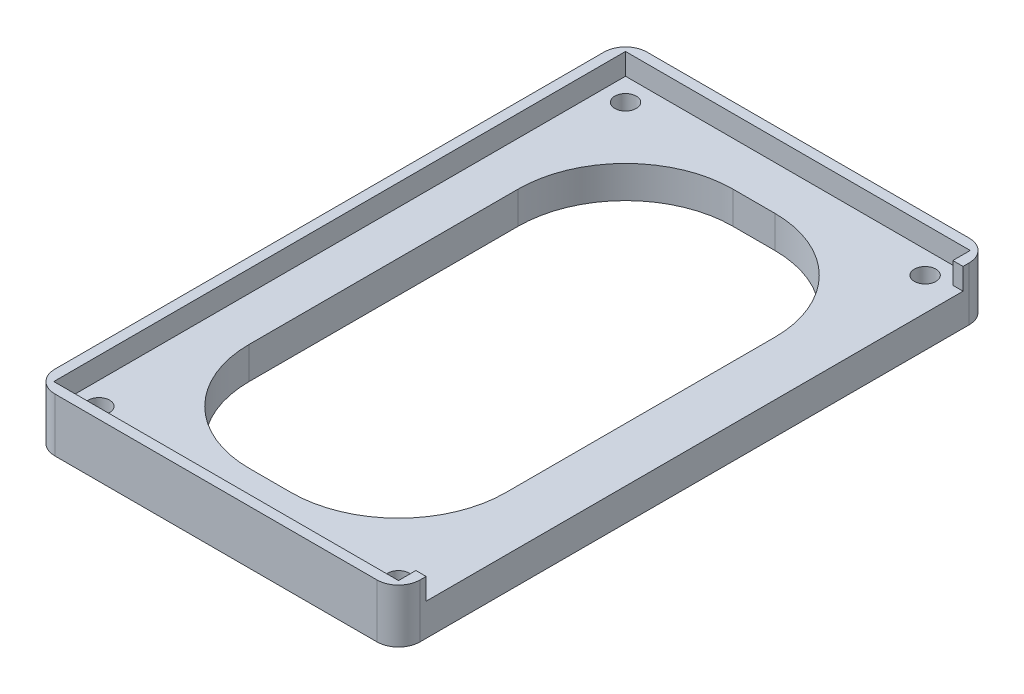
SolidWorks part; units mm, degrees
ref_plane "前视基准面" through (0, 0, 0) normal (0, 0, 1) x (1, 0, 0)
ref_plane "上视基准面" through (0, 0, 0) normal (0, 1, 0) x (1, 0, 0)
ref_plane "右视基准面" through (0, 0, 0) normal (1, 0, 0) x (0, 0, -1)
other "Configuration Table"
sketch "草图1" plane through (0, 0, 0) normal (0, 1, 0) x (1, 0, 0)
  line L1 (0, 0) -> (34, 0)
  line L2 (0, 0) -> (0, 55.14)
  line L3 (0, 55.14) -> (34, 55.14)
  line L4 (34, 0) -> (34, 55.14)
  dimension "D1" = 34
  dimension "D2" = 55.14
extrude "凸台-拉伸1" add sketch "草图1" along normal blind 5
sketch "草图2" plane through (0, 5, 0) normal (0, 1, 0) x (1, 0, 0)
  line L0 (0.95, 54.19) -> (33.05, 54.19)
  line L2 (0, 55.14) -> (0, 0)
  line L3 (0, 0) -> (34, 0)
  line L4 (34, 55.14) -> (34, 0)
  line L5 (33.05, 54.19) -> (33.05, 0.95)
  line L6 (0.95, 0.95) -> (33.05, 0.95)
  line L7 (0.95, 54.19) -> (0.95, 0.95)
  line L8 (0, 55.14) -> (34, 55.14) construction
  dimension "D1" = 0.95
extrude "切除-拉伸1" cut sketch "草图2" against normal blind 2 contours L0 L7 L6 L5
sketch "草图3" plane through (34, 0, 0) normal (1, 0, 0) x (0, 0, -1)
  line L0 (0, 5) -> (55.14, 5) construction
  line L1 (52.57, 10) -> (2.57, 10)
  line L2 (52.57, 10) -> (52.57, 0)
  line L3 (52.57, 0) -> (2.57, 0)
  line L4 (2.57, 10) -> (2.57, 0)
  line L5 (52.57, 10) -> (2.57, 0) construction
  line L6 (52.57, 0) -> (2.57, 10) construction
  line L7 (0, 0) -> (55.14, 0) construction
  point P0 (27.57, 5)
  dimension "D1" = 50
extrude "切除-拉伸2" cut sketch "草图3" against normal blind 2
fillet "圆角3" radius 2 1 edges at (0, 2.5, 0)
fillet "圆角4" radius 2 1 edges at (0, 2.5, -55.14)
fillet "圆角5" radius 2 1 edges at (34, 2.5, -55.14)
fillet "圆角6" radius 2 1 edges at (34, 2.5, 0)
sketch "草图5" plane through (0, 3, 0) normal (0, 1, 0) x (1, 0, 0)
  line L0 (17, -945.81) -> (17, 49054.19) construction
  line L1 (0.95, 54.19) -> (3.05, 54.19)
  line L2 (0.95, 54.19) -> (0.95, 52.09)
  line L3 (0.95, 52.09) -> (3.05, 52.09)
  line L4 (3.05, 54.19) -> (3.05, 52.09)
  line L6 (-999.05, 27.57) -> (49000.95, 27.57) construction
  line L7 (0.95, 54.19) -> (0.95, 0.95) construction
  line L8 (0.95, 54.19) -> (33.05, 54.19) construction
  circle A0 centre (3.05, 52.09) radius 1
  circle A1 centre (3.05, 3.05) radius 1
  circle A2 centre (30.95, 3.05) radius 1
  circle A3 centre (30.95, 52.09) radius 1
  point P13 (0.95, 27.57)
  point P16 (17, 54.19)
  dimension "D3" = 2
  dimension "D1" = 2.1
  dimension "D2" = 2.1
extrude "切除-拉伸3" cut sketch "草图5" against normal blind 5 contours A2 | A3 | A0 | A1
sketch "草图6" plane through (0, 3, 0) normal (0, 1, 0) x (1, 0, 0)
  line L0 (5.05, 49.09) -> (5.05, 6.05)
  line L1 (3.05, 52.09) -> (30.95, 52.09)
  line L2 (3.05, 52.09) -> (3.05, 3.05)
  line L3 (3.05, 3.05) -> (30.95, 3.05)
  line L4 (30.95, 52.09) -> (30.95, 3.05)
  line L5 (6.05, 5.05) -> (6.2547, 5.05)
  line L6 (28.95, 50.09) -> (28.95, 5.05)
  line L7 (6.05, 50.09) -> (6.2547, 50.09)
  line L8 (10.05, 49.09) -> (10.05, 6.05)
  line L13 (5.05, 50.09) -> (7.2547, 50.09)
  line L14 (5.05, 50.09) -> (5.05, 5.05)
  line L15 (5.05, 5.05) -> (7.2547, 5.05)
  line L16 (7.2547, 49.09) -> (7.2547, 6.05)
  line L17 (11.05, 50.09) -> (11.2547, 50.09)
  line L18 (12.2547, 49.09) -> (12.2547, 6.05)
  line L19 (11.05, 5.05) -> (11.2547, 5.05)
  line L20 (15.05, 49.09) -> (15.05, 6.05)
  line L21 (16.05, 50.09) -> (16.2547, 50.09)
  line L22 (17.2547, 49.09) -> (17.2547, 6.05)
  line L23 (16.05, 5.05) -> (16.2547, 5.05)
  line L24 (20.05, 49.09) -> (20.05, 6.05)
  line L25 (21.05, 50.09) -> (21.2547, 50.09)
  line L26 (22.2547, 49.09) -> (22.2547, 6.05)
  line L27 (21.05, 5.05) -> (21.2547, 5.05)
  line L28 (25.05, 49.09) -> (25.05, 6.05)
  line L29 (26.05, 50.09) -> (26.2547, 50.09)
  line L30 (27.2547, 49.09) -> (27.2547, 6.05)
  line L31 (26.05, 5.05) -> (26.2547, 5.05)
  line L32 (5.05, 50.09) -> (28.95, 50.09) construction
  line L33 (5.05, 5.05) -> (28.95, 5.05) construction
  line L34 (5.05, 50.09) -> (5.05, 5.05) construction
  arc A0 (6.2547, 50.09) -> (7.2547, 49.09) centre (6.2547, 49.09) cw
  arc A1 (6.2547, 5.05) -> (7.2547, 6.05) centre (6.2547, 6.05) ccw
  arc A2 (6.05, 5.05) -> (5.05, 6.05) centre (6.05, 6.05) cw
  arc A3 (5.05, 49.09) -> (6.05, 50.09) centre (6.05, 49.09) cw
  arc A4 (26.2547, 50.09) -> (27.2547, 49.09) centre (26.2547, 49.09) cw
  arc A5 (25.05, 49.09) -> (26.05, 50.09) centre (26.05, 49.09) cw
  arc A6 (26.2547, 5.05) -> (27.2547, 6.05) centre (26.2547, 6.05) ccw
  arc A7 (26.05, 5.05) -> (25.05, 6.05) centre (26.05, 6.05) cw
  arc A8 (21.2547, 5.05) -> (22.2547, 6.05) centre (21.2547, 6.05) ccw
  arc A9 (20.05, 6.05) -> (21.05, 5.05) centre (21.05, 6.05) ccw
  arc A10 (21.2547, 50.09) -> (22.2547, 49.09) centre (21.2547, 49.09) cw
  arc A11 (20.05, 49.09) -> (21.05, 50.09) centre (21.05, 49.09) cw
  arc A12 (16.2547, 50.09) -> (17.2547, 49.09) centre (16.2547, 49.09) cw
  arc A13 (15.05, 49.09) -> (16.05, 50.09) centre (16.05, 49.09) cw
  arc A14 (16.2547, 5.05) -> (17.2547, 6.05) centre (16.2547, 6.05) ccw
  arc A15 (16.05, 5.05) -> (15.05, 6.05) centre (16.05, 6.05) cw
  arc A16 (11.2547, 5.05) -> (12.2547, 6.05) centre (11.2547, 6.05) ccw
  arc A17 (10.05, 6.05) -> (11.05, 5.05) centre (11.05, 6.05) ccw
  arc A18 (11.2547, 50.09) -> (12.2547, 49.09) centre (11.2547, 49.09) cw
  arc A19 (10.05, 49.09) -> (11.05, 50.09) centre (11.05, 49.09) cw
  dimension "D3" = 1
  dimension "D4" = 1
  dimension "D1" = 2
  dimension "D2" = 5
extrude "切除-拉伸5" cut sketch "草图6" against normal blind 5 contours A3 L0 A2 L5 A1 L16 A0 L7 | A19 L8 A17 L19 A16 L18 A18 L17 | A11 L24 A9 L27 A8 L26 A10 L25 | A7 L31 A6 L30 A4 L29 A5 L28 | L20 A15 L23 A14 L22 A12 L21 A13
sketch "草图7" plane through (0, 0, 0) normal (0, -1, 0) x (1, 0, 0)
  line L1 (3.3369, -4.5252) -> (27.9146, -4.5252)
  line L2 (3.3369, -4.5252) -> (3.3369, -50.6148)
  line L3 (3.3369, -50.6148) -> (27.9146, -50.6148)
  line L4 (27.9146, -4.5252) -> (27.9146, -50.6148)
extrude "凸台-拉伸3" add sketch "草图7" against normal blind 3
sketch "草图8" plane through (0, 0, 0) normal (0, -1, 0) x (1, 0, 0)
  line L0 (17, 0) -> (17, -3)
  line L1 (2, 0) -> (32, 0) construction
  line L3 (7, -6) -> (27, -6)
  line L4 (7, -6) -> (7, 0)
  line L5 (7, 0) -> (27, 0)
  line L6 (27, -6) -> (27, 0)
  line L7 (7, -6) -> (27, 0) construction
  line L8 (7, 0) -> (27, -6) construction
  dimension "D1" = 3
  dimension "D2" = 6
  dimension "D3" = 20
extrude "凸台-拉伸5" add sketch "草图8" along normal blind 5
sketch "草图9" plane through (0, 0, 0) normal (0, -1, 0) x (1, 0, 0)
  line L0 (17, -55.14) -> (17, -52.14)
  line L1 (32, -55.14) -> (2, -55.14) construction
  line L3 (7, -55.14) -> (27, -55.14)
  line L4 (7, -55.14) -> (7, -49.14)
  line L5 (7, -49.14) -> (27, -49.14)
  line L6 (27, -55.14) -> (27, -49.14)
  line L7 (7, -55.14) -> (27, -49.14) construction
  line L8 (7, -49.14) -> (27, -55.14) construction
  dimension "D1" = 3
  dimension "D2" = 6
  dimension "D3" = 20
extrude "凸台-拉伸6" add sketch "草图9" along normal blind 5
sketch "草图10" plane through (0, 0, -55.14) normal (0, 0, -1) x (-1, 0, 0)
  line L1 (-27, -5) -> (-24, -5)
  line L2 (-27, -5) -> (-27, -2.5)
  line L3 (-27, -2.5) -> (-24, -2.5)
  line L4 (-24, -5) -> (-24, -2.5)
  line L5 (-7, -5) -> (-10, -5)
  line L6 (-7, -5) -> (-7, -2.5)
  line L7 (-7, -2.5) -> (-10, -2.5)
  line L8 (-10, -5) -> (-10, -2.5)
  circle A0 centre (-24, -2.5) radius 2
  circle A1 centre (-10, -2.5) radius 2
  dimension "D3" = 4
  dimension "D6" = 4
  dimension "D1" = 2.5
  dimension "D2" = 3
  dimension "D4" = 2.5
  dimension "D5" = 3
extrude "切除-拉伸6" cut sketch "草图10" against normal through all contours L7 A1 L8 | L8 A1 L7 | L3 A0 L4 | L4 A0 L3
fillet "圆角7" radius 2 1 edges at (7, -5, -52.14)
fillet "圆角8" radius 2 1 edges at (7, 0, -52.14)
fillet "圆角9" radius 2 1 edges at (27, -5, -52.14)
fillet "圆角10" radius 2 1 edges at (27, 0, -52.14)
fillet "圆角11" radius 2 1 edges at (7, -5, -3)
fillet "圆角12" radius 2 1 edges at (7, 0, -3)
fillet "圆角13" radius 2 1 edges at (27, -5, -3)
fillet "圆角14" radius 2 1 edges at (27, 0, -3)
sketch "草图11" plane through (0, 0, 0) normal (0, -1, 0) x (1, 0, 0)
  line L1 (32, -2.57) -> (34, -2.57)
  line L2 (32, -2.57) -> (32, -52.57)
  line L3 (32, -52.57) -> (34, -52.57)
  line L4 (34, -2.57) -> (34, -52.57)
extrude "凸台-拉伸7" add sketch "草图11" against normal blind 3
sketch "草图12" plane through (0, 0, 0) normal (0, -1, 0) x (1, 0, 0)
  line L1 (-47.3276, 61.3832) -> (39.9649, 61.3832)
  line L2 (-47.3276, 61.3832) -> (-47.3276, -59.124)
  line L3 (-47.3276, -59.124) -> (39.9649, -59.124)
  line L4 (39.9649, 61.3832) -> (39.9649, -59.124)
  line L5 (-47.3276, 61.3832) -> (39.9649, -59.124) construction
  line L6 (-47.3276, -59.124) -> (39.9649, 61.3832) construction
  point P0 (-3.6814, 1.1296)
extrude "切除-拉伸7" cut sketch "草图12" along normal blind 10
sketch "草图13" plane through (0, 0, 0) normal (0, -1, 0) x (1, 0, 0)
  line L0 (5.05, -5.05) -> (5.05, -50.09)
  line L1 (3.05, -3.05) -> (30.95, -3.05)
  line L2 (3.05, -3.05) -> (3.05, -52.09)
  line L3 (3.05, -52.09) -> (30.95, -52.09)
  line L5 (5.05, -50.09) -> (28.95, -50.09)
  line L6 (28.95, -5.05) -> (28.95, -50.09)
  line L7 (5.05, -5.05) -> (28.95, -5.05)
  line L8 (30.95, -3.05) -> (30.95, -52.09) construction
  dimension "D1" = 2
extrude "切除-拉伸8" cut sketch "草图13" against normal blind 10 contours L7 L0 L5 L6
fillet "圆角15" radius 10 1 edges at (28.95, 1.5, -50.09)
fillet "圆角16" radius 10 1 edges at (5.05, 1.5, -50.09)
fillet "圆角17" radius 10 1 edges at (28.95, 1.5, -5.05)
fillet "圆角18" radius 10 1 edges at (5.05, 1.5, -5.05)
